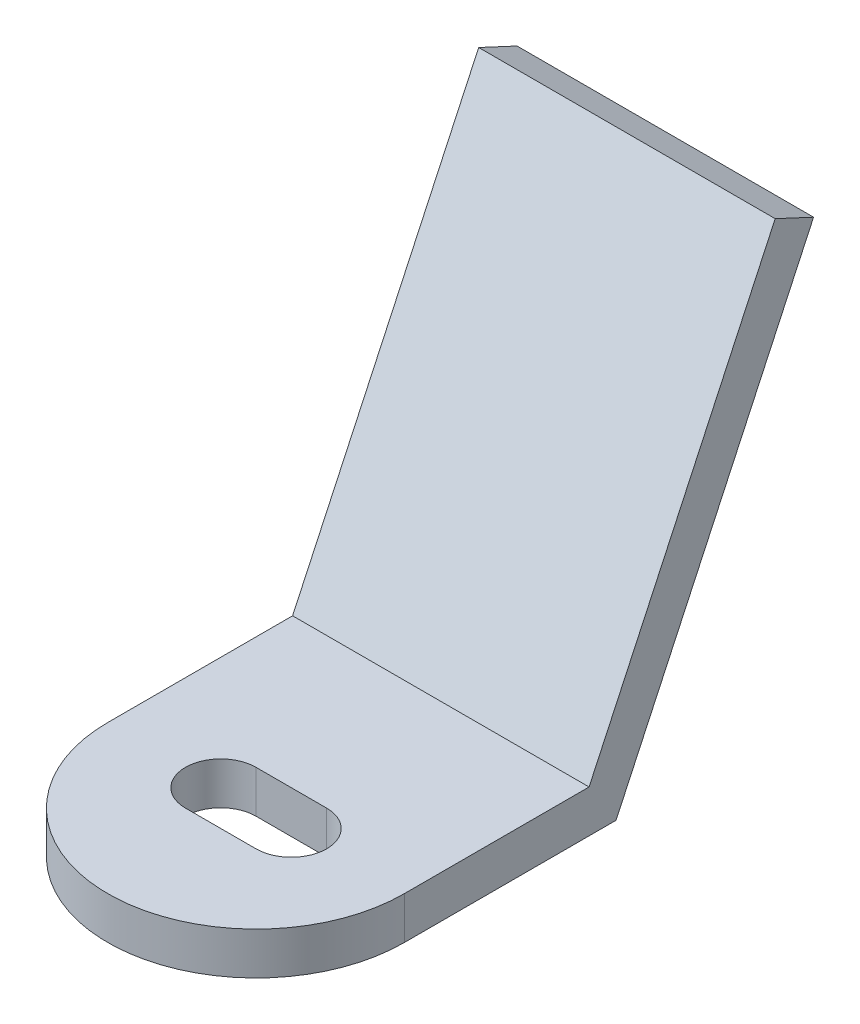
SolidWorks part; units mm, degrees
ref_plane "Front Plane" through (0, 0, 0) normal (0, 0, 1) x (1, 0, 0)
ref_plane "Top Plane" through (0, 0, 0) normal (0, 1, 0) x (1, 0, 0)
ref_plane "Right Plane" through (0, 0, 0) normal (1, 0, 0) x (0, 0, -1)
sketch "Sketch1" plane through (0, 0, 0) normal (0, 1, 0) x (1, 0, 0)
  line L0 (-10.5, 0) -> (-10.5, 15)
  line L1 (-10.5, 15) -> (10.5, 15)
  line L2 (10.5, 15) -> (10.5, 0)
  line L3 (-2.5, 0) -> (2.5, 0) construction
  line L4 (-2.5, 2.5) -> (2.5, 2.5)
  line L5 (-2.5, -2.5) -> (2.5, -2.5)
  arc A0 (-10.5, 0) -> (10.5, 0) centre (0, 0) ccw
  arc A2 (-2.5, 2.5) -> (-2.5, -2.5) centre (-2.5, 0) ccw
  arc A3 (2.5, -2.5) -> (2.5, 2.5) centre (2.5, 0) ccw
  point P8 (0, 0)
  dimension "D1" = 10.5
  dimension "D2" = 2.5
  dimension "D3" = 15
  dimension "D4" = 5
extrude "Boss-Extrude1" add sketch "Sketch1" along normal blind 3
sketch "Sketch3" plane through (10.5, 0, 0) normal (1, 0, 0) x (0, 0, -1)
  line L0 (15, 0) -> (28.9892, 30)
  line L1 (28.9892, 30) -> (26.2703, 31.2679)
  line L2 (26.2703, 31.2679) -> (11.6899, 0)
  line L3 (0, 0) -> (15, 0) construction
  line L4 (11.6899, 0) -> (15, 0)
  line L5 (15, 0) -> (63.68, 0) construction
  dimension "D1" = 65
  dimension "D2" = 3
  dimension "D3" = 3.3101
  dimension "D4" = 30
extrude "Boss-Extrude3" add sketch "Sketch3" against normal up to surface (21 mm away) up to face at (-10.5, 1.5, -7.5)
